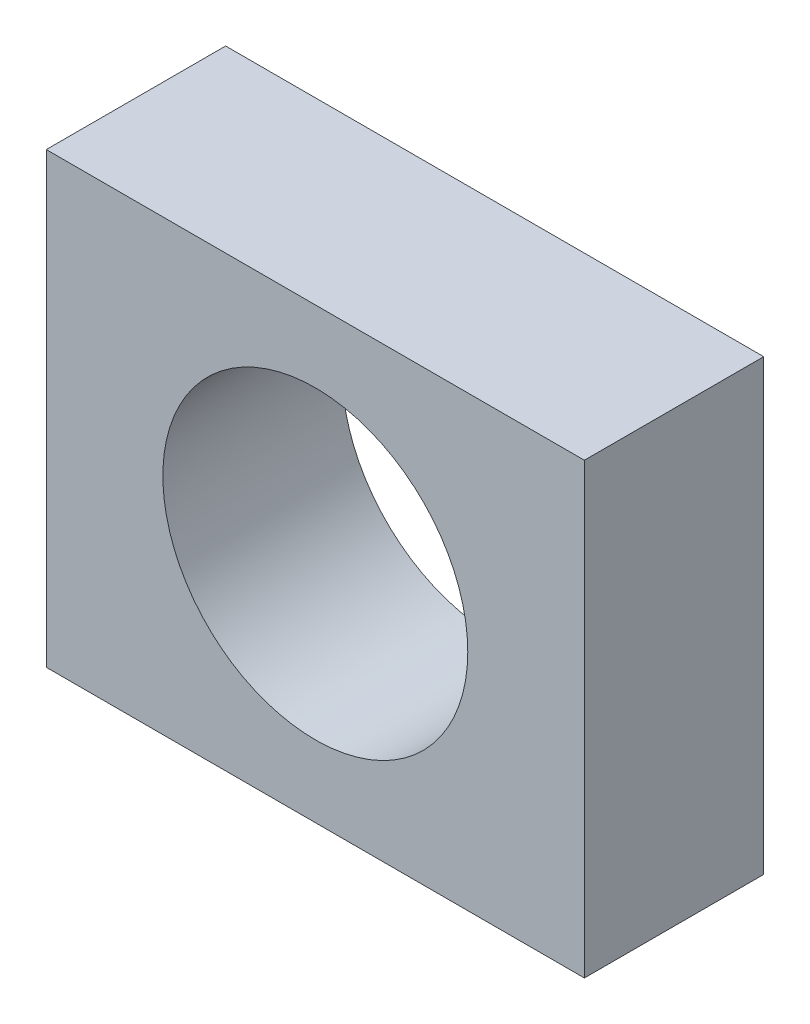
SolidWorks part; units mm, degrees
ref_plane "Front Plane" through (0, 0, 0) normal (0, 0, 1) x (1, 0, 0)
ref_plane "Top Plane" through (0, 0, 0) normal (0, 1, 0) x (1, 0, 0)
ref_plane "Right Plane" through (0, 0, 0) normal (1, 0, 0) x (0, 0, -1)
sketch "Sketch1" plane through (0, 0, 0) normal (0, 0, 1) x (1, 0, 0)
  line L1 (-1.5, -1.25) -> (1.5, -1.25)
  line L2 (-1.5, -1.25) -> (-1.5, 1.25)
  line L3 (-1.5, 1.25) -> (1.5, 1.25)
  line L4 (1.5, -1.25) -> (1.5, 1.25)
  line L5 (-1.5, -1.25) -> (1.5, 1.25) construction
  line L6 (-1.5, 1.25) -> (1.5, -1.25) construction
  circle A0 centre (0, 0) radius 0.85
  dimension "D1" = 1.7
  dimension "D2" = 3
  dimension "D3" = 2.5
extrude "Boss-Extrude1" add sketch "Sketch1" along normal blind 1
